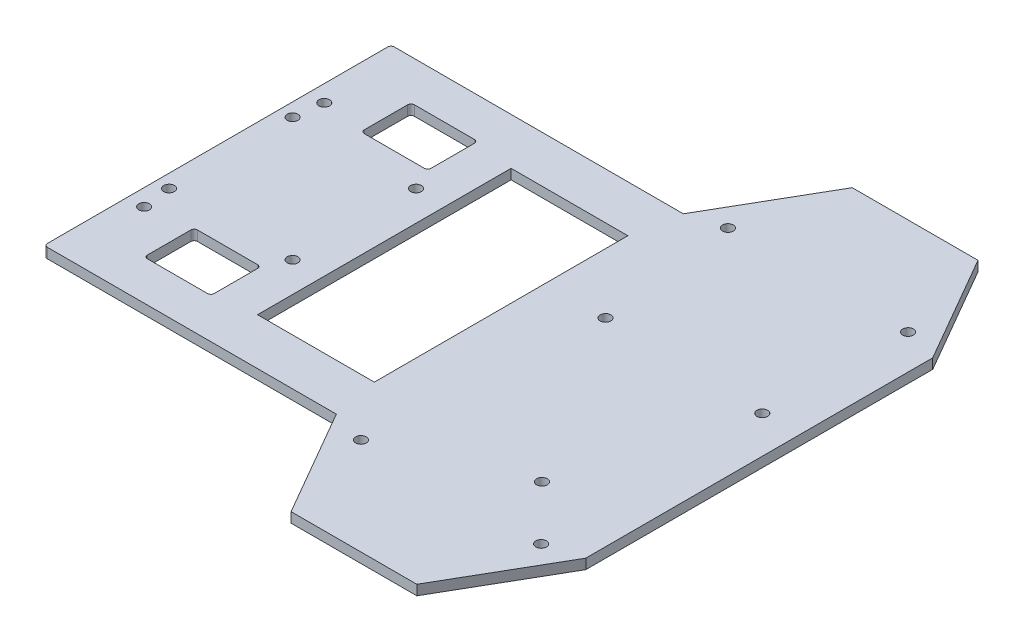
SolidWorks part; units mm, degrees
material "Acrylic (Medium-high impact)"
ref_plane "Front Plane" through (0, 0, 0) normal (0, 0, 1) x (1, 0, 0)
ref_plane "Top Plane" through (0, 0, 0) normal (0, 1, 0) x (1, 0, 0)
ref_plane "Right Plane" through (0, 0, 0) normal (1, 0, 0) x (0, 0, -1)
sketch "Sketch1" plane through (0, 0, 0) normal (0, 1, 0) x (1, 0, 0)
  line L0 (0, 52) -> (0, -52)
  line L12 (0, 52) -> (87.6171, 52)
  line L13 (87.6171, 52) -> (106.15, 84.1)
  line L14 (106.15, 84.1) -> (143.85, 84.1)
  line L15 (143.85, 84.1) -> (162.3829, 52)
  line L19 (162.3829, -52) -> (143.85, -84.1)
  line L20 (143.85, -84.1) -> (106.15, -84.1)
  line L21 (106.15, -84.1) -> (87.6171, -52)
  line L22 (87.6171, -52) -> (0, -52)
  line L23 (125, 84.1) -> (125, -84.1) construction
  line L24 (162.3829, 52) -> (162.3829, -52)
  point P7 (0, 0)
  point P12 (125, 0)
  point P15 (0, 0)
  dimension "D1" = 104
  dimension "D2" = 37.7
  dimension "D3" = 32.1
  dimension "D4" = 120
  dimension "D5" = 143.85
extrude "Boss-Extrude1" add sketch "Sketch1" along normal blind 3
fillet "Fillet1" radius 1 2 edges at (0, 1.5, 52) (0, 1.5, -52)
sketch "Sketch2" plane through (0, 3, 0) normal (0, 1, 0) x (1, 0, 0)
  line L0 (0, 51) -> (0, -51) construction
  line L1 (4, 18.5) -> (41, 18.5) construction
  line L2 (4, 18.5) -> (4, -18.5) construction
  line L3 (4, -18.5) -> (41, -18.5) construction
  line L4 (41, 18.5) -> (41, -18.5) construction
  circle A0 centre (4, 18.5) radius 1.6
  circle A1 centre (41, 18.5) radius 1.6
  circle A2 centre (4, -18.5) radius 1.6
  circle A3 centre (41, -18.5) radius 1.6
  point P4 (4, 0)
  dimension "D3" = 3.2
  dimension "D4" = 4
  dimension "D1" = 37
  dimension "D2" = 37
extrude "Motor Driver Holes" cut sketch "Sketch2" against normal through all
sketch "Sketch3" plane through (0, 3, 0) normal (0, 1, 0) x (1, 0, 0)
  line L1 (38, 25) -> (18, 25)
  line L2 (38, 25) -> (38, 40)
  line L3 (38, 40) -> (18, 40)
  line L4 (18, 25) -> (18, 40)
  circle A0 centre (41, 18.5) radius 1.6 construction
  dimension "D1" = 25
  dimension "D2" = 20
  dimension "D3" = 3
  dimension "D4" = 15
extrude "Motor Driver Routing Pocket" cut sketch "Sketch3" against normal through all
fillet "Motor Driver Routing Pocket Fillets" radius 1 4 edges at (38, 1.5, -25) (38, 1.5, -40) (18, 1.5, -25) (18, 1.5, -40)
mirror "Mirror1" about plane through (0, 0, 0) normal (0, 0, 1) of "Motor Driver Routing Pocket", "Motor Driver Routing Pocket Fillets"
sketch "Sketch5" plane through (0, 3, 0) normal (0, 1, 0) x (1, 0, 0)
  line L1 (50, -38) -> (85, -38)
  line L2 (50, -38) -> (50, 38)
  line L3 (50, 38) -> (85, 38)
  line L4 (85, -38) -> (85, 38)
  line L5 (50, -38) -> (85, 38) construction
  line L6 (50, 38) -> (85, -38) construction
  point P0 (67.5, 0)
  dimension "D1" = 76
  dimension "D2" = 35
  dimension "D3" = 50
extrude "Battery Seat" cut sketch "Sketch5" against normal through all
sketch "Sketch6" plane through (0, 3, 0) normal (0, 1, 0) x (1, 0, 0)
  circle A0 centre (136, -38.75) radius 1.6
  circle A1 centre (151.24, 12.05) radius 1.6
  circle A2 centre (102.98, 13.32) radius 1.6
  dimension "D3" = 3.2
  dimension "D1" = 38.75
  dimension "D2" = 136
  dimension "D4" = 50.8
  dimension "D5" = 15.24
  dimension "D6" = 52.07
  dimension "D7" = 33.02
extrude "Microcontroller Standoff Holes" cut sketch "Sketch6" against normal through all
sketch "Sketch8" plane through (0, 3, 0) normal (0, 1, 0) x (1, 0, 0)
  circle A0 centre (5, 27) radius 1.6
  circle A1 centre (5, -27) radius 1.6
  circle A2 centre (98, -55) radius 1.6
  circle A3 centre (98, 55) radius 1.6
  circle A4 centre (152, -55) radius 1.6
  circle A5 centre (152, 55) radius 1.6
  dimension "D1" = 3.2
  dimension "D2" = 54
  dimension "D3" = 27
  dimension "D4" = 27
  dimension "D5" = 5
  dimension "D6" = 98
  dimension "D7" = 55
  dimension "D8" = 55
extrude "Plate Standoff Holes" cut sketch "Sketch8" against normal through all
equation "\"D4@Sketch8\"=\"D3@Sketch8\""
equation "\"D8@Sketch8\"=\"D7@Sketch8\""
